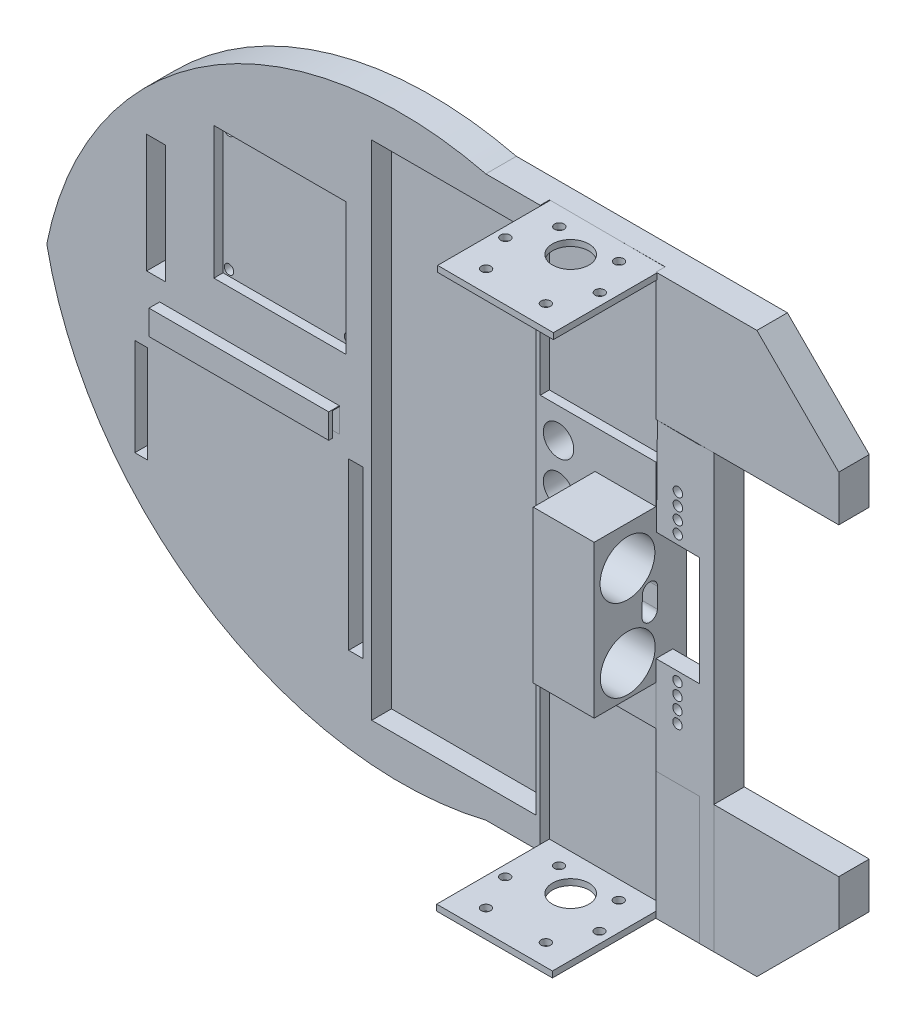
SolidWorks part; units mm, degrees
ref_plane "Front Plane" through (0, 0, 0) normal (0, 0, 1) x (1, 0, 0)
ref_plane "Top Plane" through (0, 0, 0) normal (0, 1, 0) x (1, 0, 0)
ref_plane "Right Plane" through (0, 0, 0) normal (1, 0, 0) x (0, 0, -1)
sketch "Sketch1" plane through (0, 0, 0) normal (0, 0, 1) x (1, 0, 0)
  line L1 (0, 0) -> (0, -50)
  line L2 (0, 50) -> (60, 50)
  line L3 (0, -50) -> (60, -50)
  line L4 (60, 50) -> (60, 65)
  line L5 (60, -50) -> (60, -65)
  line L6 (60, 65) -> (33.1299, 91.8701)
  line L7 (33.1299, 91.8701) -> (-55.8501, 91.8701)
  line L8 (60, -65) -> (33.1299, -91.8701)
  line L9 (33.1299, -91.8701) -> (-55.8501, -91.8701)
  line L10 (-55.8501, 91.8701) -> (-55.8501, 169.9436) construction
  line L11 (-55.8501, 169.9436) -> (-55.8501, -262.005) construction
  line L22 (0, 50) -> (0, 0)
  line L24 (-83.882, 95.237) -> (-230.9548, 95.237) construction
  line L25 (-83.882, 23.2048) -> (-83.882, 138.7176) construction
  line L26 (-83.882, -23.1381) -> (-83.882, -112.3942) construction
  line L27 (-83.882, -95.2351) -> (-171.3154, -95.2351) construction
  arc A7 (-200, -0.1322) -> (-55.8501, 91.8701) centre (-83.882, -23.1381) cw
  arc A8 (-55.8501, -91.8701) -> (-200, -0.1322) centre (-83.882, 23.2048) cw
  dimension "D11" = 199.5908
  dimension "D12" = 200
  dimension "D10" = 183.7401
  dimension "D1" = 50
  dimension "D2" = 50
  dimension "D3" = 60
  dimension "D4" = 15
  dimension "D5" = 15
  dimension "D6" = 135
  dimension "D7" = 38
  dimension "D8" = 38
  dimension "D9" = 135
  dimension "D15" = 88.98
  dimension "D16" = 88.98
extrude "Boss-Extrude1" add sketch "Sketch1" along normal blind 10 and the other way blind 0.01
sketch "Sketch3" plane through (0, 0, 10) normal (0, 0, 1) x (1, 0, 0)
  line L0 (33.1299, 91.8701) -> (-55.8501, 91.8701) construction
  line L1 (-38, 91.8701) -> (0, 91.8701)
  line L2 (-38, 91.8701) -> (-38, 37.8701)
  line L3 (-38, 37.8701) -> (0, 37.8701)
  line L4 (0, 91.8701) -> (0, 37.8701)
  dimension "D1" = 54
extrude "Cut-Extrude1" cut sketch "Sketch3" against normal blind 3 contours L2 L1 L4 L3
sketch "Sketch5" plane through (0, 0, 10) normal (0, 0, 1) x (1, 0, 0)
  line L0 (-55.8501, -91.8701) -> (33.1299, -91.8701) construction
  line L1 (-38, -37.8701) -> (0, -37.8701)
  line L2 (-38, -37.8701) -> (-38, -91.8701)
  line L3 (-38, -91.8701) -> (0, -91.8701)
  line L4 (0, -37.8701) -> (0, -91.8701)
  dimension "D1" = 54
extrude "Cut-Extrude3" cut sketch "Sketch5" against normal blind 3
sketch "Sketch7" plane through (0, 0, 10) normal (0, 0, 1) x (1, 0, 0)
  line L9 (-93.3252, 82.7857) -> (-39.3252, 82.7857)
  line L10 (-93.3252, 82.7857) -> (-93.3252, -82.2143)
  line L11 (-93.3252, -82.2143) -> (-39.3252, -82.2143)
  line L12 (-39.3252, 82.7857) -> (-39.3252, -82.2143)
  point P4 (0, 0)
  dimension "D1" = 54
  dimension "D2" = 165
extrude "Cut-Extrude4" cut sketch "Sketch7" against normal blind 6.5
sketch "Sketch8" plane through (0, 0, 10) normal (0, 0, 1) x (1, 0, 0)
  line L1 (-162.9927, 67.8133) -> (-84.7927, 67.8133)
  line L2 (-162.9927, 67.8133) -> (-162.9927, 10.3133)
  line L3 (-162.9927, 10.3133) -> (-84.7927, 10.3133)
  line L4 (-84.7927, 67.8133) -> (-84.7927, 10.3133)
  dimension "D1" = 78.2
  dimension "D2" = 57.5
extrude "Cut-Extrude5" [suppressed] cut sketch "Sketch8" against normal blind 3
sketch "Sketch9" plane through (0, 0, 10) normal (0, 0, 1) x (1, 0, 0)
  line L1 (-195, 36) -> (-176, 36)
  line L2 (-195, 36) -> (-195, 20)
  line L3 (-195, 20) -> (-176, 20)
  line L4 (-176, 36) -> (-176, 20)
  line L5 (-95.7317, 17.4542) -> (-82.493, 17.4542)
  line L6 (-95.7317, 17.4542) -> (-95.7317, 7.0108)
  line L7 (-95.7317, 7.0108) -> (-82.493, 7.0108)
  line L8 (-82.493, 17.4542) -> (-82.493, 7.0108)
  line L9 (-131.8867, -50.9252) -> (-116.9909, -50.9252)
  line L10 (-131.8867, -50.9252) -> (-131.8867, -65.1638)
  line L11 (-131.8867, -65.1638) -> (-116.9909, -65.1638)
  line L12 (-116.9909, -50.9252) -> (-116.9909, -65.1638)
extrude "Boss-Extrude2" [suppressed] add sketch "Sketch9" along normal blind 20.3
sketch "Sketch15" plane through (0, 0, 10) normal (0, 0, 1) x (1, 0, 0)
  line L0 (0, -37.8701) -> (0, 37.8701) construction
  line L1 (-20, 25.2016) -> (0, 25.2016)
  line L2 (-20, 25.2016) -> (-20, -24.7984)
  line L3 (-20, -24.7984) -> (0, -24.7984)
  line L4 (0, 25.2016) -> (0, -24.7984)
  dimension "D1" = 50
  dimension "D2" = 20
extrude "Boss-Extrude3" add sketch "Sketch15" along normal blind 20.3
sketch "Sketch16" plane through (0, 0, 10) normal (0, 0, 1) x (1, 0, 0)
  line L1 (-232.4208, 4) -> (-224.8235, 4)
  line L2 (-232.4208, 4) -> (-232.4208, -4)
  line L3 (-232.4208, -4) -> (-224.8235, -4)
  line L4 (-224.8235, 4) -> (-224.8235, -4)
  line L9 (-134.6881, 94.0493) -> (-144.6881, 94.0493)
  line L10 (-134.6881, 94.0493) -> (-134.6881, 84.6493)
  line L11 (-134.6881, 84.6493) -> (-144.6881, 84.6493)
  line L12 (-144.6881, 94.0493) -> (-144.6881, 84.6493)
  line L13 (-65.6779, 70.3488) -> (-74.3779, 70.3488)
  line L14 (-65.6779, 70.3488) -> (-65.6779, 61.8488)
  line L15 (-65.6779, 61.8488) -> (-74.3779, 61.8488)
  line L16 (-74.3779, 70.3488) -> (-74.3779, 61.8488)
  line L17 (-65.9779, -61.6233) -> (-75.3779, -61.6233)
  line L18 (-65.9779, -61.6233) -> (-65.9779, -70.9233)
  line L19 (-65.9779, -70.9233) -> (-75.3779, -70.9233)
  line L20 (-75.3779, -61.6233) -> (-75.3779, -70.9233)
  line L21 (-134.6881, -83.6815) -> (-144.6881, -83.6815)
  line L22 (-134.6881, -83.6815) -> (-134.6881, -92.9815)
  line L23 (-134.6881, -92.9815) -> (-144.6881, -92.9815)
  line L24 (-144.6881, -83.6815) -> (-144.6881, -92.9815)
extrude "Boss-Extrude4" [suppressed] add sketch "Sketch16" along normal blind 30
sketch "Sketch17" plane through (0, 0, 0) normal (0, 0, 1) x (1, 0, 0)
  circle A1 centre (-228.4208, 0) radius 2.55
  circle A2 centre (-139.6881, 89.6493) radius 3.5
  circle A3 centre (-69.8779, 66.3488) radius 3.5
  circle A4 centre (-69.8779, -66.6233) radius 3.5
  circle A5 centre (-139.6881, -88.6815) radius 3.5
extrude "Cut-Extrude17" [suppressed] cut sketch "Sketch17" along normal through all
sketch "Sketch18" plane through (0, 0, 10) normal (0, 0, 1) x (1, 0, 0)
  line L1 (-145.1245, 61) -> (-101.7245, 61)
  line L2 (-145.1245, 61) -> (-145.1245, 17.6)
  line L3 (-145.1245, 17.6) -> (-101.7245, 17.6)
  line L4 (-101.7245, 61) -> (-101.7245, 17.6)
  point P4 (0, 0)
  dimension "D1" = 43.4
  dimension "43.4" = 43.4
extrude "Cut-Extrude18" cut sketch "Sketch18" against normal blind 3
sketch "Sketch20" plane through (0, 0, 0) normal (0, 0, 1) x (1, 0, 0)
  circle A0 centre (-185.9471, 27.1121) radius 5
  circle A1 centre (-124.7094, -57.6129) radius 5
  circle A2 centre (-88.8879, 12.7504) radius 4
extrude "Cut-Extrude20" [suppressed] cut sketch "Sketch20" along normal through all
sketch "Sketch21" plane through (0, 0, 0) normal (1, 0, 0) x (0, 0, -1)
  line L0 (-3.8276, 29.0855) -> (-3.8276, -37.1575) construction
  line L1 (-6.4886, 28.3852) -> (-6.4886, -37.2976) construction
  line L2 (-5.0881, 28.1051) -> (-5.0881, -37.5777) construction
  line L3 (-11.99, 2.3019) -> (-12.0559, -4.1532) construction
  line L4 (-9.4916, 2.2764) -> (-9.5574, -4.1787)
  line L5 (-14.4885, 2.3274) -> (-14.5544, -4.1277)
  circle A0 centre (-19.3619, 12.3718) radius 9
  circle A1 centre (-19.2654, -14.6282) radius 9
  arc A2 (-9.4916, 2.2764) -> (-14.4885, 2.3274) centre (-11.99, 2.3019) ccw
  arc A3 (-14.5544, -4.1277) -> (-9.5574, -4.1787) centre (-12.0559, -4.1532) ccw
  point P12 (-12.023, -0.9256)
  dimension "D1" = 18
  dimension "D2" = 18
  dimension "D3" = 27
extrude "Cut-Extrude21" cut sketch "Sketch21" against normal up to surface (20 mm away) up to face at (-20, 0.2016, 20.15)
sketch "Sketch22" plane through (0, 0, 7) normal (0, 0, 1) x (1, 0, 0)
  circle A0 centre (-143.1686, 58.9795) radius 1.55
  circle A1 centre (-103.7686, 58.9795) radius 1.55
  circle A2 centre (-103.7686, 19.5795) radius 1.55
  circle A3 centre (-143.1686, 19.5795) radius 1.55
  point P3 (0, 0)
  dimension "D1" = 2
  dimension "D2" = 2
extrude "Cut-Extrude23" cut sketch "Sketch22" against normal through all
sketch "Sketch25" plane through (0, 0, 10) normal (0, 0, 1) x (1, 0, 0)
  line L5 (-162.9326, 1.9159) -> (-103.9326, 1.9159)
  line L6 (-162.9326, 1.9159) -> (-162.9326, -6.1841)
  line L7 (-162.9326, -6.1841) -> (-103.9326, -6.1841)
  line L8 (-103.9326, 1.9159) -> (-103.9326, -6.1841)
  dimension "D1" = 8.1
  dimension "D2" = 59
extrude "Boss-Extrude5" add sketch "Sketch25" along normal blind 3.5
sketch "Sketch26" plane through (0, -6.1841, 0) normal (0, -1, 0) x (1, 0, 0)
  line L0 (-172.679, 10.0037) -> (-152.674, 9.9893) construction
  line L1 (-152.674, 9.9893) -> (-152.6595, 14.6073) construction
extrude "Cut-Extrude24" [suppressed] cut sketch "Sketch26" against normal up to surface (58.5 mm away)
sketch "Sketch28" plane through (0, -91.8701, 0) normal (0, -1, 0) x (1, 0, 0)
  line L1 (14.2266, 10.0076) -> (18.9795, 10.0076)
  line L2 (14.2266, 10.0076) -> (14.2266, 0.0598)
  line L3 (14.2266, 0.0598) -> (18.9795, 0.0598)
  line L4 (18.9795, 10.0076) -> (18.9795, 0.0598)
extrude "Boss-Extrude6" add sketch "Sketch28" against normal up to surface (141.8701 mm away) up to face at (24, 50, 5.396)
sketch "Sketch34" plane through (0, 0, 10) normal (0, 0, 1) x (1, 0, 0)
  line L0 (0, 0) -> (85.4359, -0.2266) construction
  line L1 (53.8089, -34.3247) -> (61.9289, -40.2214)
  line L2 (53.8089, -34.3247) -> (57.1772, -29.6864)
  line L3 (61.9289, -40.2214) -> (65.2973, -35.5831)
  line L4 (57.1772, -29.6864) -> (65.2973, -35.5831)
  line L5 (62.1414, 39.8924) -> (65.4851, 35.2362)
  line L6 (57.3338, 29.3826) -> (65.4851, 35.2362)
  line L7 (53.9902, 34.0388) -> (57.3338, 29.3826)
  line L8 (53.9902, 34.0388) -> (62.1414, 39.8924)
extrude "Cut-Extrude27" [suppressed] cut sketch "Sketch34" against normal through all
sketch "Sketch36" plane through (0, 0, 7) normal (0, 0, 1) x (1, 0, 0)
  line L0 (0, 0) -> (106.9048, -0.1896) construction
  line L1 (0.3256, 91.8145) -> (0.3185, 89.8146)
  line L2 (0, -91.8151) -> (-38, -91.8151)
  line L3 (0, -91.8151) -> (0, -89.8151)
  line L4 (0, -89.8151) -> (-38, -89.8151)
  line L5 (-38, -91.8151) -> (-38, -89.8151)
  line L6 (-37.6741, 91.9493) -> (-37.6812, 89.9493)
  line L7 (0.3185, 89.8146) -> (-37.6812, 89.9493)
  line L8 (0.3256, 91.8145) -> (-37.6741, 91.9493)
  point P14 (0, 0)
  dimension "D1" = 2
extrude "Boss-Extrude7" add sketch "Sketch36" along normal blind 37
sketch "Sketch39" plane through (0, -91.8151, 0) normal (0, -1, 0) x (1, 0, 0)
  line L1 (-46.4365, 25) -> (22.9075, 25) construction
  line L4 (31.9978, 332) -> (-461.8231, 332) construction
  circle A1 centre (-19, 19) radius 6
  circle A2 centre (-34.4996, 25.0106) radius 1.55
  circle A3 centre (-3.5639, 24.9888) radius 1.55
  circle A4 centre (-28.8192, 37.0106) radius 1.55
  circle A5 centre (-9.1774, 36.9888) radius 1.55
  circle A6 centre (-28.82, 13.0106) radius 1.55
  circle A7 centre (-9.2305, 12.9888) radius 1.55
  point P18 (6.9989, 178.85)
  dimension "D1" = 12
  dimension "D5" = 12
  dimension "D6" = 12
  dimension "D7" = 12
  dimension "D8" = 12
  dimension "D2" = 19
extrude "Cut-Extrude28" cut sketch "Sketch39" against normal up to surface (2 mm away) up to face at (-19, -89.8151, 20.3333)
sketch "Sketch42" plane through (0.3256, 91.8145, 0) normal (0.0035, 1, 0) x (1, -0.0035, 0)
  circle A7 centre (-19.3258, -19) radius 6
  circle A9 centre (-29.0701, -13) radius 1.55
  circle A10 centre (-3.7784, -25) radius 1.55
  circle A11 centre (-9.4641, -13) radius 1.55
  circle A12 centre (-34.7723, -25) radius 1.55
  circle A13 centre (-29.0965, -37) radius 1.55
  circle A14 centre (-9.4734, -37) radius 1.55
  dimension "D1" = 12
  dimension "D5" = 6
  dimension "D6" = 6
  dimension "D7" = 6
  dimension "D8" = 6
  dimension "D9" = 18
  dimension "D10" = 18
  dimension "D2" = 19
extrude "Cut-Extrude29" cut sketch "Sketch42" against normal up to surface (2 mm away) up to face at (-12.4542, 89.8599, 20.3333)
sketch "Sketch44" plane through (-162.9326, 0, 0) normal (-1, 0, 0) x (0, 0, 1)
  line L1 (12.2622, 1.6288) -> (10.0122, 1.6288)
  line L2 (12.2622, 1.6288) -> (12.2622, -6.1912)
  line L3 (12.2622, -6.1912) -> (10.0122, -6.1912)
  line L4 (10.0122, 1.6288) -> (10.0122, -6.1912)
  point P4 (0, 0)
  dimension "D1" = 2.25
  dimension "D2" = 7.82
extrude "Cut-Extrude30" cut sketch "Sketch44" against normal up to surface (59 mm away) up to face at (-103.9326, -2.1341, 11.75)
sketch "Sketch45" plane through (0, 0, -0.01) normal (0, 0, -1) x (-1, 0, 0)
  line L0 (0, 0) -> (-86.1371, -0.4083) construction
  line L13 (-0.1707, 17.9992) -> (-0.474, 49.9978)
  line L14 (-16.5, -18) -> (0, -18)
  line L15 (-16.5, -18) -> (-16.5, -50)
  line L16 (-16.5, -50) -> (0, -50)
  line L17 (0, -18) -> (0, -50)
  line L18 (-16.9733, 49.8413) -> (-0.474, 49.9978)
  line L19 (-16.6699, 17.8428) -> (-16.9733, 49.8413)
  line L20 (-16.6699, 17.8428) -> (-0.1707, 17.9992)
extrude "Boss-Extrude8" add sketch "Sketch45" against normal up to surface (10.0176 mm away) up to face at (16.6031, -20.935, 10.0076)
sketch "Sketch30" plane through (0, 0, -0.01) normal (0, 0, -1) x (-1, 0, 0)
  line L0 (0.5881, -0.0011) -> (-26.6848, -0.0585) construction
  line L1 (0, -41.01) -> (-14.12, -41.01)
  line L2 (0, -41.01) -> (0, -16.01)
  line L3 (0, -16.01) -> (-14.12, -16.01)
  line L4 (-14.12, -41.01) -> (-14.12, -16.01)
  line L5 (-14.2924, 40.9456) -> (-14.1872, 15.9458)
  line L6 (-0.0674, 16.0052) -> (-14.1872, 15.9458)
  line L7 (-0.1725, 41.005) -> (-0.0674, 16.0052)
  line L8 (-0.1725, 41.005) -> (-14.2924, 40.9456)
  point P6 (0, 0)
  point P11 (0, 0)
  point P12 (0, 0)
  point P13 (0, 0)
  point P14 (0, 0)
  point P15 (0, 0)
  point P16 (0, 0)
  point P17 (0, 0)
  point P18 (0, 0)
  point P19 (0, 0)
  point P20 (0, 0)
  dimension "D1" = 25
  dimension "D2" = 14.12
extrude "Cut-Extrude25" cut sketch "Sketch30" against normal blind 4.5
sketch "Sketch33" plane through (0, 0, -0.01) normal (0, 0, -1) x (-1, 0, 0)
  line L0 (0, 0) -> (-115.8951, -0.2361) construction
  circle A0 centre (-7.06, -33) radius 1.55
  circle A1 centre (-7.06, -29) radius 1.55
  circle A2 centre (-7.06, -25) radius 1.55
  circle A3 centre (-7.06, -21) radius 1.55
  circle A4 centre (-7.1455, 20.9711) radius 1.55
  circle A5 centre (-7.1618, 24.971) radius 1.55
  circle A6 centre (-7.1781, 28.971) radius 1.55
  circle A7 centre (-7.1944, 32.971) radius 1.55
  point P18 (0, 0)
  point P19 (0, 0)
  point P20 (0, 0)
  point P21 (0, 0)
  dimension "D1" = 4
extrude "Cut-Extrude26" cut sketch "Sketch33" against normal up to surface (10.0176 mm away) up to face at (9.5356, -8.3699, 10.0076)
sketch "Sketch46" plane through (0, 0, 10) normal (0, 0, 1) x (1, 0, 0)
  circle A0 centre (-32, 28) radius 5
  circle A1 centre (-32, 14) radius 5
  circle A2 centre (-32, 0) radius 5
  circle A3 centre (-32, -14) radius 5
  circle A4 centre (-32, -28) radius 5
  point P2 (0, 0)
  dimension "D1" = 5
extrude "Cut-Extrude31" cut sketch "Sketch46" against normal through all
sketch "Sketch47" plane through (0, 0, 10) normal (0, 0, 1) x (1, 0, 0)
  line L1 (-167.202, 47.4765) -> (-161.0629, 47.4765)
  line L2 (-167.202, 47.4765) -> (-167.202, 8.5957)
  line L3 (-167.202, 8.5957) -> (-161.0629, 8.5957)
  line L4 (-161.0629, 47.4765) -> (-161.0629, 8.5957)
  line L5 (-100.9, -11.6633) -> (-96.1934, -11.6633)
  line L6 (-100.9, -11.6633) -> (-100.9, -66.0964)
  line L7 (-100.9, -66.0964) -> (-96.1934, -66.0964)
  line L8 (-96.1934, -11.6633) -> (-96.1934, -66.0964)
  line L9 (-171.0901, -13.0957) -> (-166.9973, -13.0957)
  line L10 (-171.0901, -13.0957) -> (-171.0901, -45.0189)
  line L11 (-171.0901, -45.0189) -> (-166.9973, -45.0189)
  line L12 (-166.9973, -13.0957) -> (-166.9973, -45.0189)
extrude "Cut-Extrude32" cut sketch "Sketch47" against normal through all
